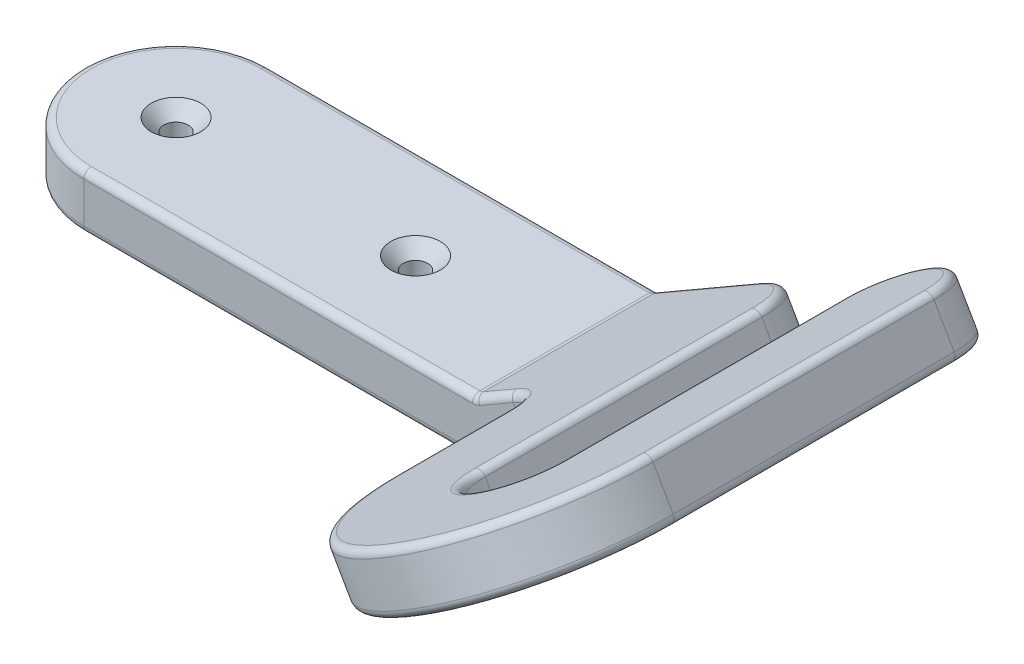
SolidWorks part; units mm, degrees
material "1.0570 (S355J2G3)"
ref_plane "Front Plane" through (0, 0, 0) normal (0, 0, 1) x (1, 0, 0)
ref_plane "Top Plane" through (0, 0, 0) normal (0, 1, 0) x (1, 0, 0)
ref_plane "Right Plane" through (0, 0, 0) normal (1, 0, 0) x (0, 0, -1)
sketch "Sketch1" plane through (0, 0, 0) normal (0, 1, 0) x (1, 0, 0)
  line L1 (-55, 25) -> (55, 25)
  line L3 (-55, -25) -> (55, -25)
  line L4 (55, 25) -> (55, -25)
  line L5 (-55, 25) -> (55, -25) construction
  line L6 (-55, -25) -> (55, 25) construction
  arc A0 (-55, 25) -> (-55, -25) centre (-55, 0) ccw
  point P0 (0, 0)
  point P7 (-80, 0)
  dimension "D1" = 50
  dimension "D2" = 135
extrude "Boss-Extrude1" add sketch "Sketch1" along normal blind 15
sketch "Sketch2" plane through (0, 0, -25) normal (0, 0, -1) x (-1, 0, 0)
  line L2 (-76.6506, 12.5) -> (-55, 0)
  line L5 (-55, 0) -> (55, 0) construction
  line L8 (-76.6506, 12.5) -> (-69.1506, 25.4904)
  line L9 (-69.1506, 25.4904) -> (-50.9808, 15)
  line L10 (-55, 15) -> (55, 15) construction
  line L11 (-50.9808, 15) -> (-55, 0)
  dimension "D1" = 210
  dimension "D2" = 25
  dimension "D3" = 15
extrude "Boss-Extrude2" add sketch "Sketch2" against normal up to surface (50 mm away) up to face at (0, 7.5, 25)
sketch "Sketch3" plane through (13.75, -23.8157, 0) normal (0.5, -0.866, 0) x (0.866, 0.5, 0)
  line L0 (100.1314, 65) -> (100.1314, -10)
  line L2 (72.6314, 35) -> (72.6314, 65)
  line L4 (125.1314, 65) -> (125.1314, -11.25)
  line L5 (152.6314, 65) -> (152.6314, -11.25)
  line L6 (72.6314, -25) -> (47.6314, -25) construction
  line L7 (62.6314, -25) -> (62.6314, 25)
  line L8 (-47.6314, 25) -> (47.6314, 25) construction
  line L9 (62.6314, -25) -> (85.1314, -25)
  arc A0 (100.1314, 65) -> (125.1314, 65) centre (112.6314, 65) cw
  arc A2 (62.6314, 25) -> (72.6314, 35) centre (62.6314, 35) ccw
  arc A3 (72.6314, 65) -> (152.6314, 65) centre (112.6314, 65) cw
  arc A4 (125.1314, -11.25) -> (152.6314, -11.25) centre (138.8814, -11.25) ccw
  arc A5 (100.1314, -10) -> (85.1314, -25) centre (85.1314, -10) cw
  point P17 (112.6314, 105)
  point P18 (138.8814, -25)
  dimension "D1" = 15
  dimension "D3" = 10
  dimension "D2" = 40
  dimension "D4" = 27.5
  dimension "D5" = 80
  dimension "D7" = 130
  dimension "D8" = 25
extrude "Boss-Extrude3" add sketch "Sketch3" against normal blind 15
hole_wizard "CSK for M5 Flat Head Machine Screw1" positions "Sketch4" profile "Sketch5" countersink size "M5" standard "ANSI Metric" end condition up to next
sketch "Sketch4" plane through (0, 15, 0) normal (0, 1, 0) x (1, 0, 0)
  point P0 (-55, 0)
  point P3 (10, 0)
  dimension "D1" = 65
sketch "Sketch5" plane through (-55, 15, 0) normal (1, 0, 0) x (0, 0, 1)
  line L0 (0, 0) -> (0, 15)
  line L1 (0, 15) -> (3.3, 15)
  line L2 (3.3, 15) -> (3.3, 3.42)
  line L3 (3.3, 3.42) -> (6.72, 0)
  line L5 (6.72, 0) -> (0, 0)
  line L6 (-3.3, 3.42) -> (-6.72, 0) construction
  line L11 (0, -6.35) -> (0, 107.95) construction
  dimension "Thru Hole Dia." = 6.6
  dimension "Thru Hole Depth" = 15
  dimension "Near C'Sink Dia." = 13.44
  dimension "Near C'Sink Angle" = 90
fillet "Fillet1" radius 17 1 edges at (55, 0, 0)
fillet "Fillet2" radius 2 31 edges at (100.4663, 26.25, 27.5) (92.9663, 39.2404, 27.5) (111.2917, 32.5, 77.5) (103.7917, 45.4904, 77.5) (122.117, 38.75, 26.875) (114.617, 51.7404, 26.875) (134.0248, 45.625, -25) (126.5248, 58.6154, -25) (145.9327, 52.5, 26.875) (138.4327, 65.4904, 26.875) (111.2917, 32.5, 105) (103.7917, 45.4904, 105) (76.6506, 12.5, 50) (69.1506, 25.4904, 50) (74.1141, 11.0355, 27.9289) (66.6141, 24.0259, 27.9289) (55.7356, 17.7452, 25) (65.4784, 23.3702, -25) (-2.0096, 15, -25) (-80, 15, 0) (63.4676, 4.8888, 25) (73.2104, 10.5138, -25) (54.8448, 0.5793, -25) (-2.2776, 0, -25) (-80, 0, 0) (54.8448, 0.5793, 25) (-2.0096, 15, 25) (-2.2776, 0, 25) (50.9808, 15, 0) (96.6615, 24.0533, -20.6066) (89.1615, 37.0437, -20.6066)
